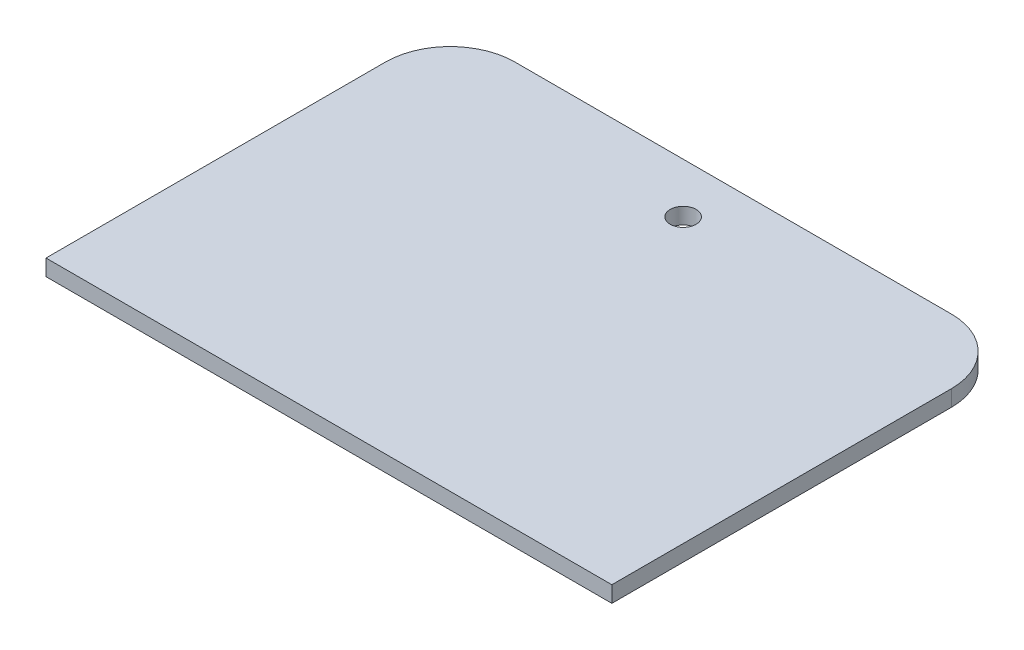
SolidWorks part; units mm, degrees
material "Poliestireno"
ref_plane "Alzado" through (0, 0, 0) normal (0, 0, 1) x (1, 0, 0)
ref_plane "Planta" through (0, 0, 0) normal (0, 1, 0) x (1, 0, 0)
ref_plane "Vista lateral" through (0, 0, 0) normal (1, 0, 0) x (0, 0, -1)
sketch "Croquis1" plane through (0, 0, 0) normal (0, 1, 0) x (1, 0, 0)
  line L1 (-35, 25) -> (35, 25)
  line L2 (-35, 25) -> (-35, -25)
  line L3 (-35, -25) -> (35, -25)
  line L4 (35, 25) -> (35, -25)
  line L5 (-35, 25) -> (35, -25) construction
  line L6 (-35, -25) -> (35, 25) construction
  point P0 (0, 0)
  dimension "D1" = 50
  dimension "D2" = 70
extrude "Saliente-Extruir1" add sketch "Croquis1" along normal blind 2
fillet "Redondeo1" radius 8 2 edges at (35, 1, -25) (-35, 1, -25)
sketch "Croquis2" plane through (0, 2, 0) normal (0, 1, 0) x (1, 0, 0)
  line L0 (27, 25) -> (-27, 25) construction
  line L1 (0, 53.2843) -> (0, 25) construction
  line L2 (-10, 25) -> (10, 25)
  arc A0 (-10, 25) -> (10, 25) centre (0, 53.2843) ccw
  dimension "D2" = 30
  dimension "D1" = 20
extrude "Cortar-Extruir1" [suppressed] cut sketch "Croquis2" against normal up to next contours A0 L2
sketch "Croquis3" plane through (0, 2, 0) normal (0, 1, 0) x (1, 0, 0)
  circle A1 centre (0, 18.8197) radius 1.6
  dimension "D1" = 3.2
extrude "Cortar-Extruir2" cut sketch "Croquis3" against normal up to next
